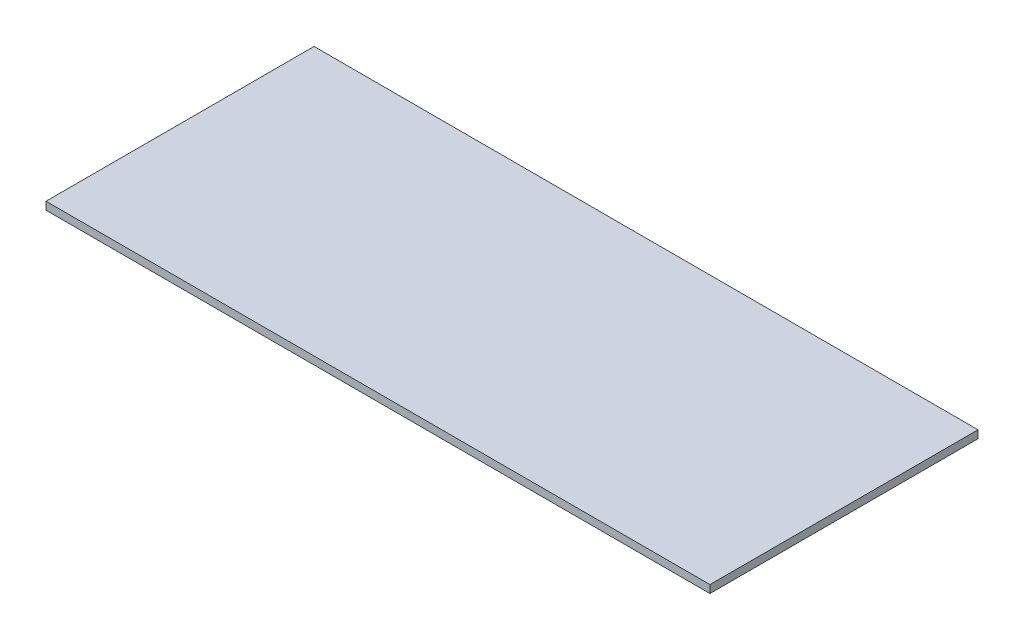
SolidWorks part; units mm, degrees
ref_plane "Front Plane" through (0, 0, 0) normal (0, 0, 1) x (1, 0, 0)
ref_plane "Top Plane" through (0, 0, 0) normal (0, 1, 0) x (1, 0, 0)
ref_plane "Right Plane" through (0, 0, 0) normal (1, 0, 0) x (0, 0, -1)
sketch "Sketch1" plane through (0, 0, 0) normal (0, 1, 0) x (1, 0, 0)
  line L1 (0, 0) -> (406.4, 0)
  line L2 (0, 0) -> (0, 164.084)
  line L3 (0, 164.084) -> (406.4, 164.084)
  line L4 (406.4, 0) -> (406.4, 164.084)
extrude "Boss-Extrude1" add sketch "Sketch1" along normal blind 4.7625 contours L2 L1 L4 L3
